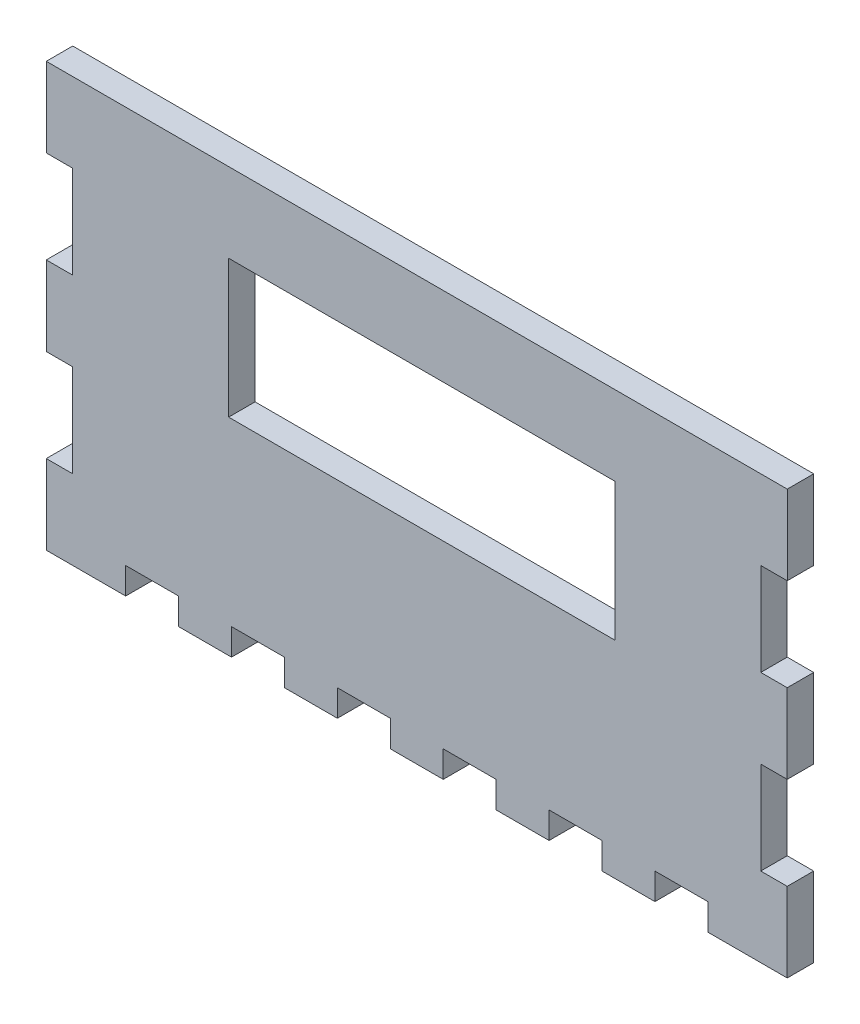
SolidWorks part; units mm, degrees
ref_plane "Front Plane" through (0, 0, 0) normal (0, 0, 1) x (1, 0, 0)
ref_plane "Top Plane" through (0, 0, 0) normal (0, 1, 0) x (1, 0, 0)
ref_plane "Right Plane" through (0, 0, 0) normal (1, 0, 0) x (0, 0, -1)
sketch "Sketch1" plane through (0, 0, 0) normal (0, 0, 1) x (1, 0, 0)
  line L0 (69.0386, -4.6833) -> (64.0386, -4.6833)
  line L1 (-55.9553, -32.1833) -> (-45.9553, -32.1833)
  line L2 (44.0447, -32.1833) -> (54.0447, -32.1833)
  line L3 (-35.9553, -32.1833) -> (-25.9553, -32.1833)
  line L4 (4.0447, -32.1833) -> (14.0447, -32.1833)
  line L5 (-65.9553, 27.8167) -> (-65.9553, 10.3167)
  line L6 (-65.9553, -4.6833) -> (-65.9553, -22.1833)
  line L7 (-70.9553, 42.8167) -> (69.0447, 42.8167)
  line L8 (-45.9553, -37.1833) -> (-35.9553, -37.1833)
  line L9 (-70.9553, -37.1833) -> (-55.9553, -37.1833)
  line L10 (69.0447, 42.8167) -> (69.0447, 27.8167)
  line L11 (64.0386, -4.6833) -> (64.0386, -22.1833)
  line L14 (69.0386, -37.1833) -> (69.0386, -22.1833)
  line L15 (69.0386, -22.1833) -> (64.0386, -22.1833)
  line L16 (-70.9553, -37.1833) -> (-55.9553, -37.1833)
  line L17 (69.0386, -4.6833) -> (69.0386, 10.3167)
  line L18 (69.0386, 10.3167) -> (64.0386, 10.3167)
  line L20 (-65.9553, -4.6833) -> (-70.9553, -4.6833)
  line L21 (69.0386, -37.1833) -> (54.0447, -37.1833)
  line L23 (-55.9553, -37.1833) -> (-55.9553, -32.1833)
  line L24 (-65.9553, 27.8167) -> (-70.9553, 27.8167)
  line L25 (-70.9553, 42.8167) -> (-70.9553, 27.8167)
  line L28 (-65.9553, -22.1833) -> (-70.9553, -22.1833)
  line L29 (-70.9553, -37.1833) -> (-70.9553, -22.1833)
  line L30 (-45.9553, -37.1833) -> (-45.9553, -32.1833)
  line L31 (-65.9553, 10.3167) -> (-70.9553, 10.3167)
  line L32 (-70.9553, -4.6833) -> (-70.9553, 10.3167)
  line L34 (-70.9553, 27.8167) -> (-65.9553, 27.8167)
  line L36 (-70.9553, 10.3167) -> (-65.9553, 10.3167)
  line L37 (-65.9553, 27.8167) -> (-65.9553, 10.3167)
  line L38 (-70.9553, -4.6833) -> (-65.9553, -4.6833)
  line L40 (-70.9553, -22.1833) -> (-65.9553, -22.1833)
  line L41 (-65.9553, -4.6833) -> (-65.9553, -22.1833)
  line L42 (64.0386, -4.6833) -> (69.0386, -4.6833)
  line L43 (64.0386, -4.6833) -> (64.0386, -22.1833)
  line L44 (64.0386, -22.1833) -> (69.0386, -22.1833)
  line L46 (64.0386, 27.8167) -> (69.0447, 27.8167)
  line L47 (64.0386, 27.8167) -> (64.0386, 10.3167)
  line L48 (64.0386, 10.3167) -> (69.0386, 10.3167)
  line L50 (-15.9553, -37.1833) -> (-15.9553, -32.1833)
  line L51 (-25.9553, -37.1833) -> (-15.9553, -37.1833)
  line L52 (-45.9553, -32.1833) -> (-45.9553, -37.1833)
  line L55 (-35.9553, -37.1833) -> (-35.9553, -32.1833)
  line L60 (-15.9553, -37.1833) -> (-15.9553, -32.1833)
  line L61 (-25.9553, -37.1833) -> (-25.9553, -32.1833)
  line L62 (-15.9553, -32.1833) -> (-5.9553, -32.1833)
  line L64 (-5.9553, -37.1833) -> (4.0447, -37.1833)
  line L65 (-15.9553, -37.1833) -> (-15.9553, -32.1833)
  line L67 (-15.9553, -37.1833) -> (-15.9553, -32.1833)
  line L82 (-5.9553, -37.1833) -> (-5.9553, -32.1833)
  line L90 (14.0447, -37.1833) -> (24.0447, -37.1833)
  line L93 (4.0447, -37.1833) -> (4.0447, -32.1833)
  line L99 (14.0447, -37.1833) -> (14.0447, -32.1833)
  line L100 (24.0447, -32.1833) -> (34.0447, -32.1833)
  line L102 (34.0447, -37.1833) -> (44.0447, -37.1833)
  line L104 (34.0447, -37.1833) -> (34.0447, -32.1833)
  line L105 (24.0447, -37.1833) -> (24.0447, -32.1833)
  line L109 (34.0447, -37.1833) -> (34.0447, -32.1833)
  line L111 (34.0447, -37.1833) -> (34.0447, -32.1833)
  line L116 (54.0447, -37.1833) -> (54.0447, -32.1833)
  line L117 (44.0447, -37.1833) -> (44.0447, -32.1833)
  dimension "D1" = 10
  dimension "D3" = 140
  dimension "D4" = 80
extrude "Boss-Extrude1" add sketch "Sketch1" along normal blind 5
sketch "Sketch3" plane through (0, 0, 5) normal (0, 0, 1) x (1, 0, 0)
  line L0 (-70.9553, 42.8167) -> (69.0447, 42.8167) construction
  line L1 (-36.5, 1.8167) -> (36.5, 1.8167)
  line L2 (-36.5, 1.8167) -> (-36.5, 27.8167)
  line L3 (-36.5, 27.8167) -> (36.5, 27.8167)
  line L4 (36.5, 1.8167) -> (36.5, 27.8167)
  point P0 (0, 0)
  dimension "D1" = 73
  dimension "D2" = 26
  dimension "D3" = 15
extrude "Cut-Extrude1" cut sketch "Sketch3" against normal through all contours L3 L4 L1 L2
